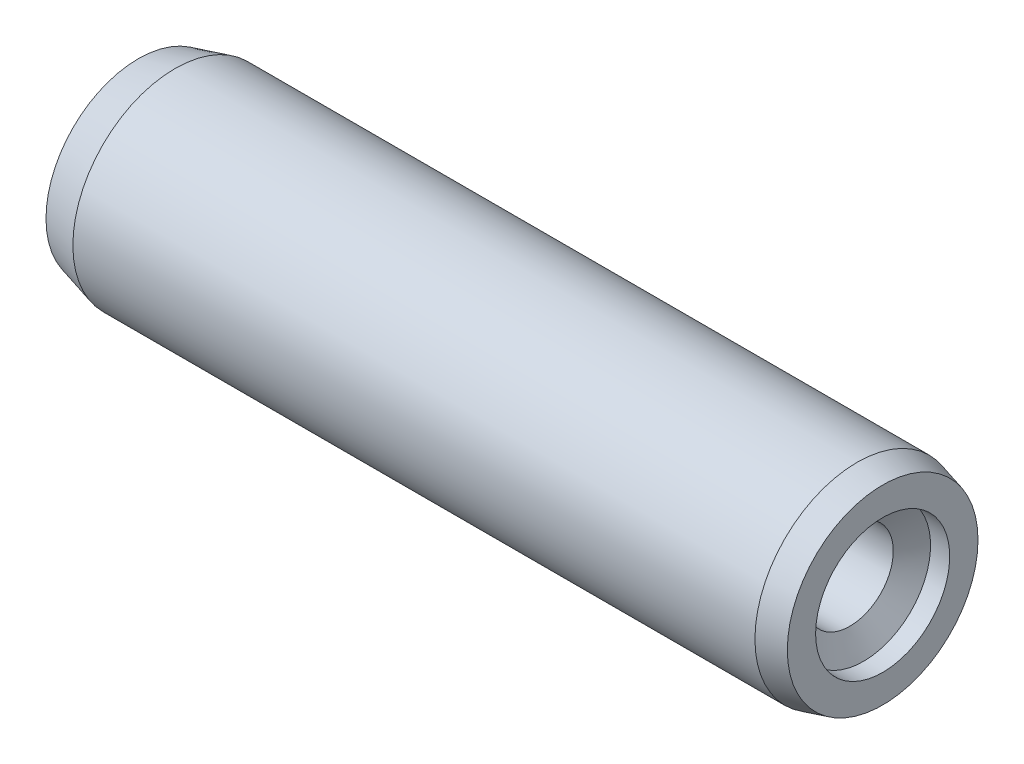
SolidWorks part; units mm, degrees
revolve "Body" add sketch "BodySke" angle 360 about L0
sketch "BodySke" plane through (0, 0, 0) normal (0, 0, 1) x (1, 0, 0)
  line L0 (0, 0) -> (66, 0) construction
  line L1 (0, 0) -> (40, 0) construction
  line L2 (4.6, 8) -> (58, 8)
  line L3 (58, 8) -> (60, 7.4641)
  line L4 (0, 0) -> (33.5917, 0)
  line L5 (60, 7.4641) -> (60, 5.25)
  line L6 (60, 5.25) -> (58.5, 5.25)
  line L7 (58.5, 5.25) -> (57.4319, 3.4)
  line L8 (57.4319, 3.4) -> (35, 3.4)
  line L9 (35, 3.4) -> (33.5917, 0)
  line L10 (57.25, 7) -> (57.25, 3) construction
  line L11 (44, 16) -> (44, 0) construction
  line L12 (4.6, 8) -> (1.7268, 7.2301)
  arc A0 (1.7268, 7.2301) -> (0, 0) centre (16, 0) ccw
  dimension "Crown_rad" = 16
  dimension "D1" = 75
  dimension "Head_ch_len" = 2
  dimension "Cbore_dia" = 10.5
  dimension "Cbore_dep" = 1.5
  dimension "Tapdrill_dia" = 6.8
  dimension "Tapdrill_dep" = 25
  dimension "D3" = 67.5
  dimension "Length" = 60
  dimension "D4" = 30
  dimension "Advance" = 1.25
  dimension "Thread_dep" = 16
  dimension "Diameter" = 16
  dimension "D2" = 165
  dimension "Tip_ch_len" = 4.6
cosmetic thread "ThreadCosmetic" [suppressed]
ref_plane "Plane1" through (0, 0, 0) normal (0, 0, 1) x (1, 0, 0)
ref_plane "Plane2" through (0, 0, 0) normal (0, 1, 0) x (1, 0, 0)
ref_plane "Plane3" through (0, 0, 0) normal (1, 0, 0) x (0, 0, -1)
sketch "ThdSchSke" plane through (0, 0, 0) normal (0, 0, 1) x (1, 0, 0)
  line L0 (57.7783, 4) -> (58.2618, 3.3095)
  line L2 (57.7783, 4) -> (57.2948, 3.3095)
  line L3 (57.2948, 3.3095) -> (58.2618, 3.3095)
  line L4 (57.7783, 5.8566) -> (57.7783, 1.7596) construction
  line L5 (27, 0) -> (36, 0) construction
  line L6 (0, 0) -> (66, 0) construction
  line L7 (60, -7.4641) -> (60, 7.4641) construction
  dimension "D1" = 70
revolve "ThreadSchematic" [suppressed] cut sketch "ThdSchSke" angle 360 about L5
pattern_linear "ThdSchPat" [suppressed]
equation "' \"Diameter@BodySke\" = 16"
equation "' \"Head_ch_len@BodySke\" = 2"
equation "' \"Tip_ch_len@BodySke\" = 4.6"
equation "' \"Thread_major@ThreadCosmetic\"  = 8"
equation "' \"Thread_major@ThreadCosmetic\" = 8"
equation "' \"Advance@BodySke\" = 1.25"
equation "' \"Cbore_dia@BodySke\" = 10.5"
equation "' \"Thread_dep@BodySke\"  = 16"
equation "' \"Thread_dep@BodySke\" = 16"
equation "' \"Tapdrill_dep@BodySke\" = 25"
equation "' \"Cbore_dep@BodySke\" = 1.5"
equation "' \"Tapdrill_dia@BodySke\" = 6.8"
equation "' \"Thread_minor@ThdSchSke\" = 6.619"
equation "'  \"Length@BodySke\" = 60"
equation "' \"Diameter@BodySke\" = 30"
equation "' \"Head_ch_len@BodySke\" = 4"
equation "' \"Tip_ch_len@BodySke\" = 7"
equation "' \"Thread_major@ThreadCosmetic\"  = 20"
equation "' \"Thread_major@ThreadCosmetic\" = 20"
equation "' \"Advance@BodySke\" = 2.5"
equation "' \"Cbore_dia@BodySke\" = 21"
equation "' \"Thread_dep@BodySke\"  = 30"
equation "' \"Thread_dep@BodySke\" = 30"
equation "' \"Tapdrill_dep@BodySke\" = 40"
equation "' \"Cbore_dep@BodySke\" = 2"
equation "' \"Tapdrill_dia@BodySke\" = 17.5"
equation "' \"Thread_minor@ThdSchSke\" = 17.252"
equation "\"Crown_rad@BodySke\" = \"Diameter@BodySke\" "
equation "\"Depth@ThreadCosmetic\" = \"Thread_dep@BodySke\"  -  \"Cbore_dep@BodySke\""
equation "\"Thread_nominal@ThdSchSke\" = \"Thread_major@ThreadCosmetic\""
equation "\"Inset@ThdSchSke\" = \"Cbore_dep@BodySke\" + (\"Cbore_dia@BodySke\" - \"Thread_major@ThreadCosmetic\") / 2 * tan(30 * 0.0174533)"
equation "\"Num_threads@ThdSchPat\" = int(  ( \"Thread_dep@BodySke\"  - \"Inset@ThdSchSke\" ) / \"Advance@BodySke\" + 0.999 )  + 1"
equation "\"Advance@ThdSchPat\" = (  \"Thread_dep@BodySke\" - \"Inset@ThdSchSke\" ) /  (\"Num_threads@ThdSchPat\" - 1) 'relax it"
